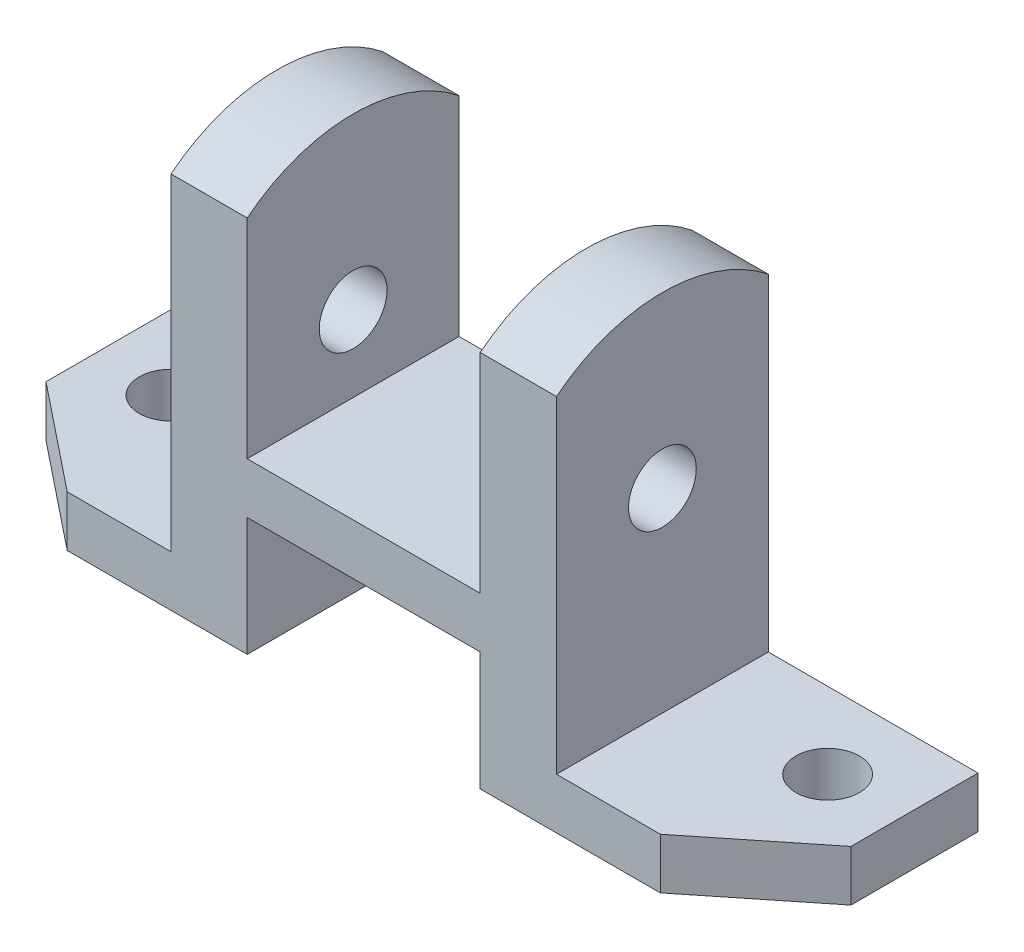
SolidWorks part; units mm, degrees
ref_plane "Front Plane" through (0, 0, 0) normal (0, 0, 1) x (1, 0, 0)
ref_plane "Top Plane" through (0, 0, 0) normal (0, 1, 0) x (1, 0, 0)
ref_plane "Right Plane" through (0, 0, 0) normal (1, 0, 0) x (0, 0, -1)
sketch "Sketch1" plane through (0, 0, 0) normal (0, 1, 0) x (1, 0, 0)
  line L0 (0, -25) -> (0, 25) construction
  line L1 (-95, -25) -> (95, -25)
  line L2 (-95, -25) -> (-95, 25)
  line L3 (-95, 25) -> (95, 25)
  line L4 (95, -25) -> (95, 25)
  line L5 (-12.9716, 0) -> (12.3156, 0) construction
  line L6 (-95, -5) -> (-70, -25)
  line L7 (95, -5) -> (70, -25)
  circle A0 centre (-77.5, 7) radius 7.5
  circle A1 centre (77.5, 7) radius 7.5
  point P0 (0, 0)
  dimension "D3" = 15
  dimension "D1" = 190
  dimension "D2" = 50
  dimension "D4" = 18
  dimension "D5" = 25
  dimension "D6" = 20
  dimension "D7" = 155
extrude "Boss-Extrude1" add sketch "Sketch1" along normal blind 98 contours L7 L4 L3 L2 L6 L1 A0 A1
sketch "Sketch2" plane through (0, 0, 25) normal (0, 0, 1) x (1, 0, 0)
  line L0 (-95, 0) -> (95, 0)
  line L1 (0, 0) -> (0, 98) construction
  line L2 (-70, 98) -> (70, 98) construction
  line L3 (-95, 0) -> (-95, 12)
  line L4 (-95, 98) -> (-95, 0) construction
  line L5 (-95, 12) -> (-45.5, 12)
  line L6 (-45.5, 12) -> (-45.5, 98)
  line L7 (-45.5, 98) -> (-27.5, 98)
  line L8 (-27.5, 98) -> (-27.5, 40)
  line L9 (-27.5, 40) -> (27.5, 40)
  line L10 (95, 12) -> (45.5, 12)
  line L11 (45.5, 12) -> (45.5, 98)
  line L12 (45.5, 98) -> (27.5, 98)
  line L13 (27.5, 98) -> (27.5, 40)
  line L14 (-27.5, 40) -> (-27.5, 28) construction
  line L15 (-27.5, 28) -> (27.5, 28)
  line L16 (-27.5, 28) -> (-27.5, 0)
  line L17 (-27.5, 0) -> (27.5, 0)
  line L18 (27.5, 28) -> (27.5, 0)
  line L19 (27.5, 40) -> (27.5, 28) construction
  line L20 (-95, 12) -> (-95, 98)
  line L21 (-95, 98) -> (-45.5, 98)
  line L22 (45.5, 98) -> (95, 98)
  line L23 (95, 98) -> (95, 12)
  line L24 (-27.5, 98) -> (27.5, 98)
  point P21 (0, 40)
  line M2 (70, 0) -> (70, 98)
  line M3 (70, 98) -> (-70, 98)
  line M4 (-70, 98) -> (-70, 0)
  dimension "D1" = 12
  dimension "D2" = 55
  dimension "D3" = 58
  dimension "D4" = 12
  dimension "D5" = 18
extrude "Cut-Extrude1" cut sketch "Sketch2" against normal through all contours L21 L20 L5 M4 | L5 L6 M3 M4 | L13 L8 L9 M3 | L11 L10 M2 M3 | L23 L22 L10 M2 | L16 L15 L18 L17
sketch "Sketch3" plane through (0, 28, 0) normal (0, -1, 0) x (1, 0, 0)
  line L0 (-77.5, -7) -> (77.5, -7) construction
  line L1 (-27.5, -11) -> (27.5, -11)
  line L2 (-77.5, -11) -> (77.5, -11) construction
  line L3 (27.5, -25) -> (27.5, 25) construction
  line L4 (-27.5, -25) -> (-27.5, 25) construction
  line L5 (27.5, -25) -> (27.5, 25)
  line L6 (-27.5, -25) -> (-27.5, 25)
  line L7 (-27.5, -3) -> (27.5, -3)
  line L8 (71.1557, -3) -> (77.5, -3)
  line L9 (71.1557, -11) -> (77.5, -11)
  circle A0 centre (77.5, -7) radius 7.5 construction
  circle A1 centre (-77.5, -7) radius 7.5 construction
  circle A2 centre (77.5, -7) radius 7.5
  circle A3 centre (-77.5, -7) radius 7.5
  point P19 (0, -11)
  line M7 (27.5, -25) -> (27.5, 25)
  dimension "D1" = 8
extrude "Boss-Extrude2" add sketch "Sketch3" along normal up to surface (28 mm away) contours L7 L6 L1 M7 up to face at (-63, 0, 1)
sketch "Sketch4" plane through (45.5, 0, 0) normal (1, 0, 0) x (0, 0, -1)
  line L0 (25, 98) -> (-25, 98) construction
  line L1 (25, 12) -> (25, 98) construction
  line L2 (-25, 12) -> (-25, 98) construction
  line L3 (25, 12) -> (25, 98)
  line L4 (-25, 12) -> (-25, 98)
  line L5 (-25, 89.225) -> (-25, 98)
  line L6 (25, 98) -> (25, 89.225)
  line L7 (-25, 98) -> (25, 98)
  circle A0 centre (0, 58) radius 8
  arc A1 (25, 89.225) -> (-25, 89.225) centre (0, 58) ccw
  line M3 (-25, 98) -> (-25, 12)
  line M6 (25, 98) -> (-25, 98)
  dimension "D1" = 16
  dimension "D2" = 40
extrude "Cut-Extrude2" cut sketch "Sketch4" against normal up to surface (91 mm away) contours A0 | A1 L7 M3 | A1 L3 M6 up to face at (-45.5, 55, 0)
